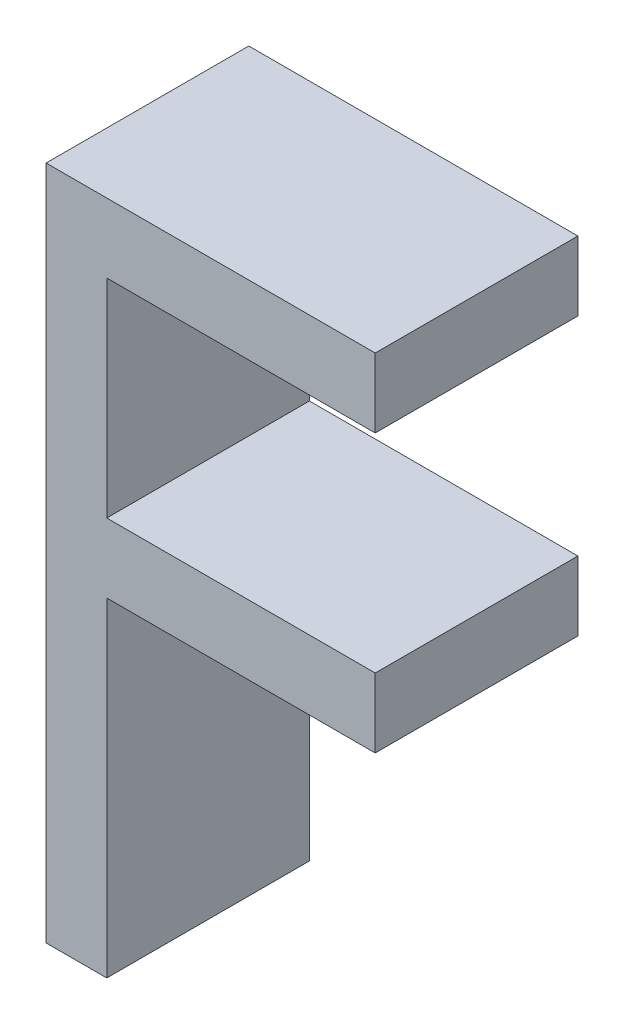
SolidWorks part; units mm, degrees
ref_plane "Plan de face" through (0, 0, 0) normal (0, 0, 1) x (1, 0, 0)
ref_plane "Plan de dessus" through (0, 0, 0) normal (0, 1, 0) x (1, 0, 0)
ref_plane "Plan de droite" through (0, 0, 0) normal (1, 0, 0) x (0, 0, -1)
sketch "Esquisse1" plane through (0, 0, 0) normal (0, 0, 1) x (1, 0, 0)
  text T0 "F" font "Century Gothic" height 5
extrude "Boss.-Extru.1" add sketch "Esquisse1" along normal blind 1.5
